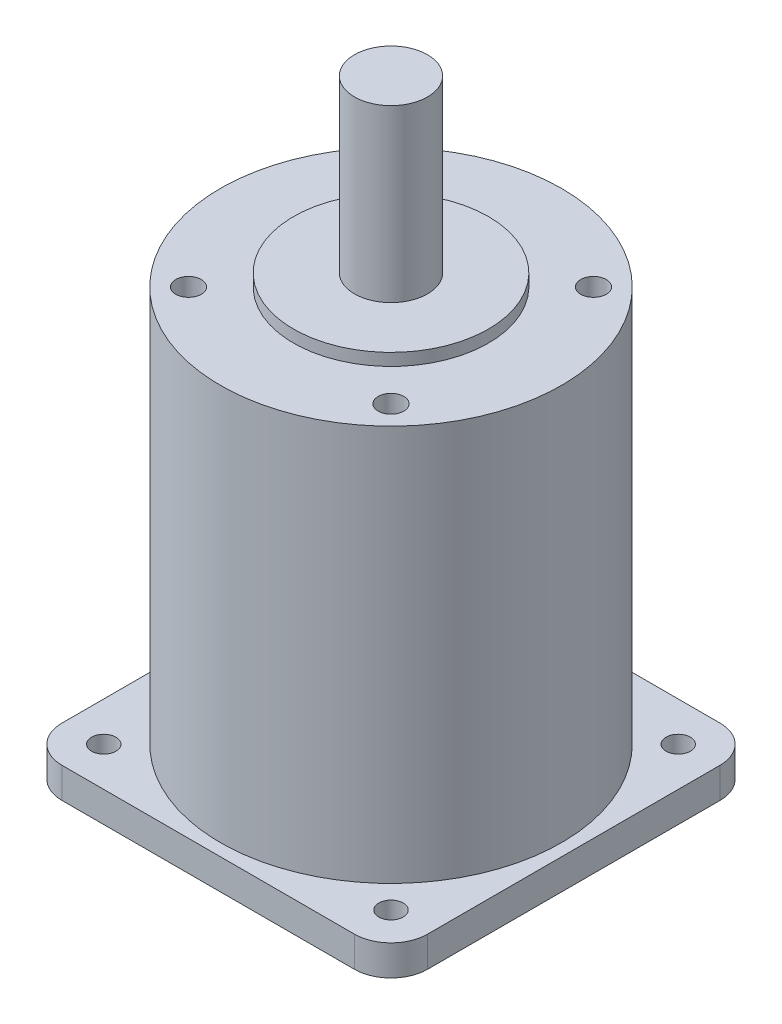
SolidWorks part; units mm, degrees
material "1.5714 (16NiCr4)"
ref_plane "Plan de face" through (0, 0, 0) normal (0, 0, 1) x (1, 0, 0)
ref_plane "Plan de dessus" through (0, 0, 0) normal (0, 1, 0) x (1, 0, 0)
ref_plane "Plan de droite" through (0, 0, 0) normal (1, 0, 0) x (0, 0, -1)
sketch "Esquisse1" plane through (0, 0, 0) normal (0, 0, 1) x (1, 0, 0)
  line L0 (0, 0) -> (0, 116.9608) construction
  line L1 (0, 0) -> (28, 0)
  line L2 (28, 0) -> (28, 65)
  line L3 (28, 65) -> (16, 65)
  line L4 (16, 65) -> (16, 67)
  line L5 (16, 67) -> (6, 67)
  line L6 (6, 67) -> (6, 95)
  line L7 (6, 95) -> (0, 95)
  line L8 (0, 95) -> (0, 0)
  line L9 (28, 0) -> (28, -5) construction
  line L10 (28, -5) -> (0, -5) construction
  line L11 (0, -5) -> (0, 0) construction
  dimension "D1" = 28
  dimension "D2" = 72
  dimension "D3" = 2
  dimension "D4" = 28
  dimension "D5" = 6
  dimension "D6" = 16
  dimension "D7" = 5
revolve "Révolution1" add sketch "Esquisse1" angle 360 about L0
sketch "Esquisse2" plane through (0, 0, 0) normal (0, -1, 0) x (1, 0, 0)
  line L0 (0, 0) -> (0, 30) construction
  line L1 (-30, 30) -> (30, 30)
  line L2 (-30, 30) -> (-30, -30)
  line L3 (-30, -30) -> (30, -30)
  line L4 (30, 30) -> (30, -30)
  line L5 (0, 0) -> (-30, 0) construction
  dimension "D1" = 60
extrude "Boss.-Extru.1" add sketch "Esquisse2" along normal blind 5
sketch "Esquisse3" plane through (0, -5, 0) normal (0, -1, 0) x (1, 0, 0)
  line L0 (0, 0) -> (0, 23.57) construction
  line L1 (-23.57, 23.57) -> (23.57, 23.57) construction
  line L2 (-23.57, 23.57) -> (-23.57, -23.57) construction
  line L3 (-23.57, -23.57) -> (23.57, -23.57) construction
  line L4 (23.57, 23.57) -> (23.57, -23.57) construction
  line L5 (0, 0) -> (-23.57, 0) construction
  circle A0 centre (-23.57, 23.57) radius 2
  circle A1 centre (23.57, 23.57) radius 2
  circle A2 centre (-23.57, -23.57) radius 2
  circle A3 centre (23.57, -23.57) radius 2
  dimension "D2" = 4
  dimension "D1" = 47.14
extrude "Enlèv. mat.-Extru.1" cut sketch "Esquisse3" against normal blind 5
fillet "Congé1" radius 6 4 edges at (-30, -2.5, -30) (30, -2.5, -30) (30, -2.5, 30) (-30, -2.5, 30)
sketch "Esquisse4" plane through (0, 65, 0) normal (0, 1, 0) x (1, 0, 0)
  line L0 (-23.57, 23.57) -> (23.57, -23.57) construction
  line L1 (-23.57, -23.57) -> (23.57, 23.57) construction
  circle A0 centre (0, 0) radius 23.5 construction
  point P11 (-16.617, 16.617)
  point P12 (-16.617, -16.617)
  point P13 (16.617, -16.617)
  point P14 (16.617, 16.617)
  dimension "D1" = 47
hole_wizard "Trou taraudé M51" positions "Esquisse6" profile "Esquisse5" tap size "M5" standard "Din"
sketch "Esquisse6" plane through (0, 65, 0) normal (0, 1, 0) x (1, 0, 0)
  point P0 (-16.617, 16.617)
  point P3 (16.617, 16.617)
  point P6 (16.617, -16.617)
  point P9 (-16.617, -16.617)
sketch "Esquisse5" plane through (-16.617, 65, -16.617) normal (1, 0, 0) x (0, 0, 1)
  line L0 (0, 0) -> (0, 25.2618)
  line L1 (0, 25.2618) -> (2.1, 24)
  line L2 (2.1, 24) -> (2.1, 0)
  line L5 (2.1, 0) -> (0, 0)
  line L10 (0, 25.2618) -> (-2.1, 24) construction
  line L11 (0, -6.35) -> (0, 107.95) construction
  dimension "Diamètre du trou pour taraudage" = 4.2
  dimension "Profondeur du trou pour taraudage" = 24
  dimension "Angle de pointe" = 118
cosmetic thread "Filetage de perçage1" parameters "D1"=20, "D2"=5
cosmetic thread "Filetage de perçage2" parameters "D1"=20, "D2"=5
cosmetic thread "Filetage de perçage3" parameters "D1"=20, "D2"=5
cosmetic thread "Filetage de perçage4" parameters "D1"=20, "D2"=5
